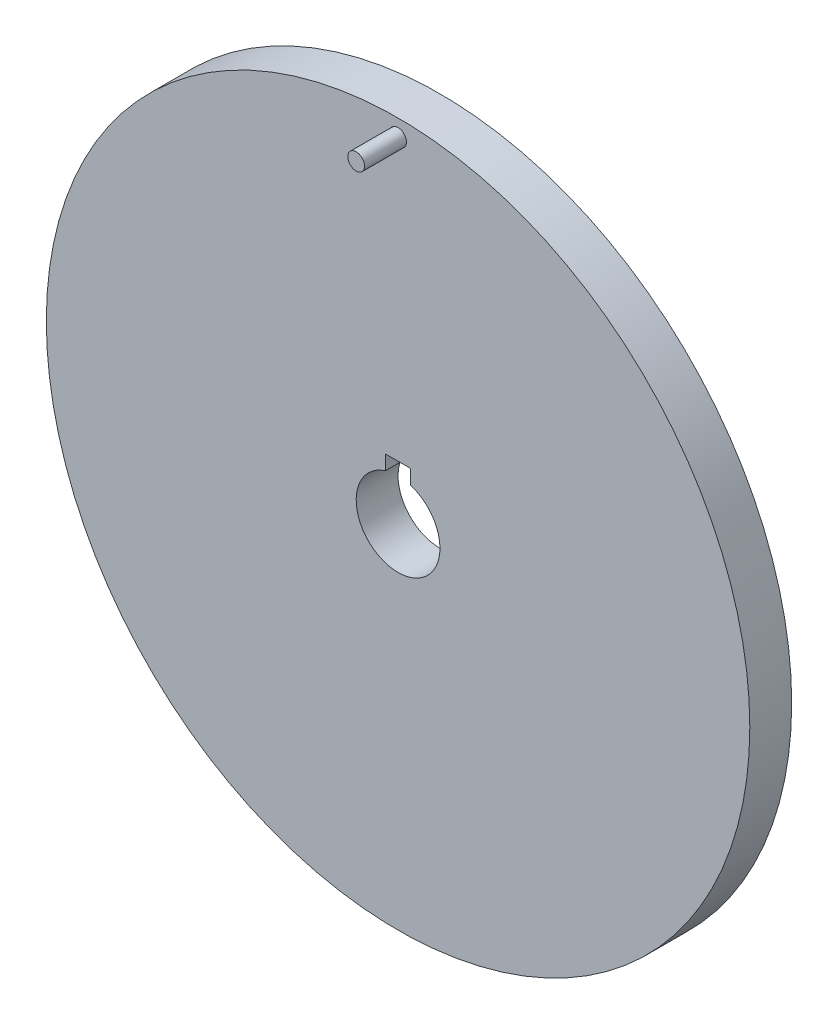
SolidWorks part; units mm, degrees
ref_plane "前视基准面" through (0, 0, 0) normal (0, 0, 1) x (1, 0, 0)
ref_plane "上视基准面" through (0, 0, 0) normal (0, 1, 0) x (1, 0, 0)
ref_plane "右视基准面" through (0, 0, 0) normal (1, 0, 0) x (0, 0, -1)
sketch "草图2" plane through (0, 0, 0) normal (0, 0, 1) x (1, 0, 0)
  circle A0 centre (0, 0) radius 42
  circle A1 centre (0, 40) radius 1
  dimension "D1" = 84
  dimension "D2" = 40
  dimension "D3" = 2
extrude "凸台-拉伸1" add sketch "草图2" along normal blind 5 contours A1 | A0 A1
sketch "草图3" plane through (0, 0, 5) normal (0, 0, 1) x (1, 0, 0)
  circle A0 centre (0, 40) radius 1
  dimension "D1" = 2
  dimension "D2" = 40
extrude "凸台-拉伸2" add sketch "草图3" along normal blind 5
sketch "草图4" plane through (0, 0, 5) normal (0, 0, 1) x (1, 0, 0)
  circle A0 centre (0, 0) radius 5
  dimension "D1" = 10
extrude "切除-拉伸1" cut sketch "草图4" against normal blind 5
sketch "草图5" plane through (0, 0, 5) normal (0, 0, 1) x (1, 0, 0)
  line L0 (-1.5, 0) -> (1.5, 0)
  line L2 (-1.5, 0) -> (-1.5, 6.5)
  line L3 (-1.5, 6.5) -> (1.5, 6.5)
  line L4 (1.5, 0) -> (1.5, 6.5)
  line L5 (0, 0) -> (1.5, 6.5) construction
  line L6 (-1.5, 6.5) -> (0, 0) construction
  point P2 (0, 0)
extrude "切除-拉伸2" cut sketch "草图5" against normal blind 5
sketch "草图6" plane through (0, 0, 0) normal (0, 0, 1) x (1, 0, 0)
  circle A0 centre (0, 0) radius 28.5
  circle A1 centre (0, 26) radius 1
  dimension "D1" = 57
  dimension "D2" = 26
  dimension "D3" = 2
